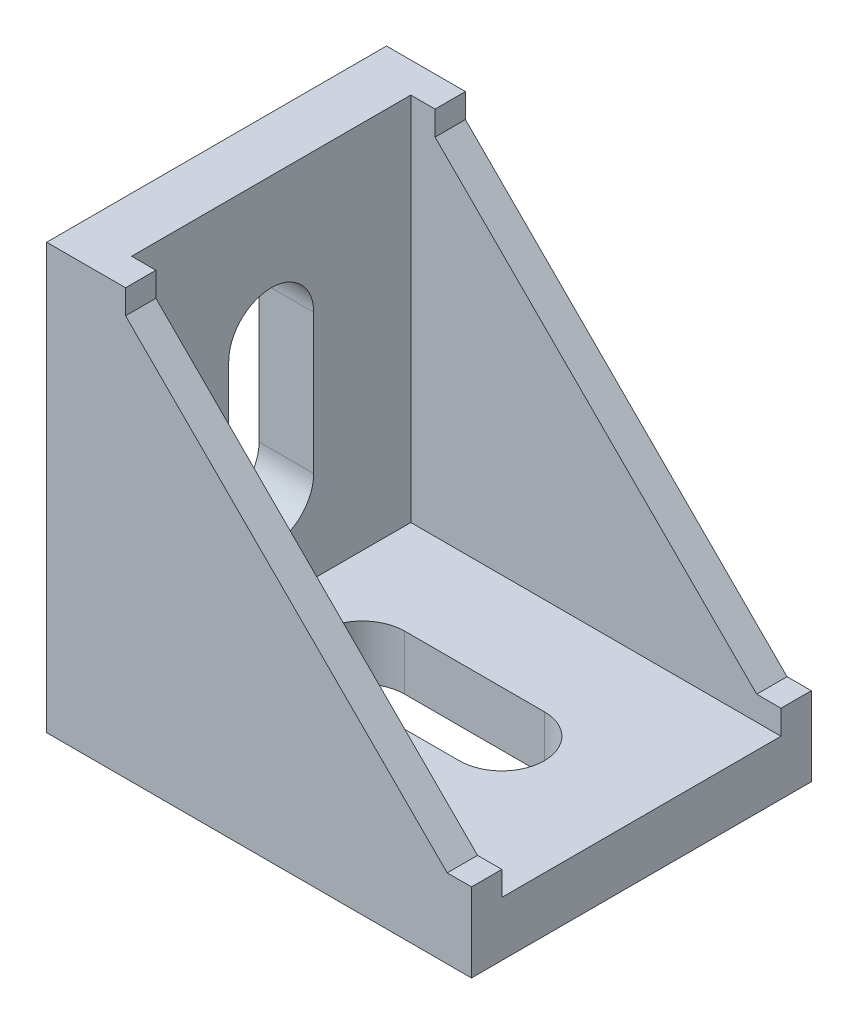
SolidWorks part; units mm, degrees
ref_plane "Front Plane" through (0, 0, 0) normal (0, 0, 1) x (1, 0, 0)
ref_plane "Top Plane" through (0, 0, 0) normal (0, 1, 0) x (1, 0, 0)
ref_plane "Right Plane" through (0, 0, 0) normal (1, 0, 0) x (0, 0, -1)
sketch "Sketch1" plane through (0, 0, 0) normal (0, 0, 1) x (1, 0, 0)
  line L1 (0, 0) -> (35, 0)
  line L2 (0, 0) -> (0, 35)
  line L3 (0, 35) -> (35, 35)
  line L4 (35, 0) -> (35, 35)
extrude "Boss-Extrude1" add sketch "Sketch1" along normal blind 28
sketch "Sketch2" plane through (0, 0, 28) normal (0, 0, 1) x (1, 0, 0)
  line L2 (6.5, 35) -> (6.5, 0)
  line L3 (6.5, 37.082) -> (6.5, 33)
  line L5 (6.5, 37.082) -> (39.7013, 37.082)
  line L6 (39.7013, 37.082) -> (39.7013, 6.5)
  line L10 (6.5, 33) -> (33, 6.5)
  line L13 (33, 6.5) -> (39.7013, 6.5)
  dimension "D1" = 6.5
extrude "Cut-Extrude1" cut sketch "Sketch2" against normal through all
ref_plane "Plane1" through (4.5, 0, 0) normal (-1, 0, 0) x (0, 0, 1)
sketch "Sketch3" plane through (4.5, 0, 0) normal (-1, 0, 0) x (0, 0, 1)
  line L2 (28, 4.5) -> (0, 4.5)
  line L3 (25.5, 4.5) -> (2.5, 4.5)
  line L5 (25.5, 33) -> (25.5, 6.5)
  line L6 (25.5, 38.217) -> (25.5, 4.5)
  line L7 (25.5, 38.217) -> (2.5, 38.217)
  line L8 (2.5, 33) -> (2.5, 6.5)
  line L9 (2.5, 38.217) -> (2.5, 4.5)
  dimension "D1" = 4.5
  dimension "D2" = 2.5
  dimension "D3" = 2.5
extrude "Cut-Extrude2" cut sketch "Sketch3" against normal up to surface (30.5 mm away) up to face at (35, 3.25, 14)
sketch "Sketch4" plane through (4.5, 0, 0) normal (1, 0, 0) x (0, 0, -1)
  line L4 (-10.5, 23.5) -> (-10.5, 12)
  line L5 (-17.5, 12) -> (-17.5, 23.5)
  arc A0 (-10.5, 23.5) -> (-17.5, 23.5) centre (-14, 23.5) ccw
  arc A1 (-17.5, 12) -> (-10.5, 12) centre (-14, 12) ccw
extrude "Cut-Extrude3" cut sketch "Sketch4" against normal up to surface (4.5 mm away) up to face at (0, 17.5, 14)
sketch "Sketch5" plane through (0, 4.5, 0) normal (0, 1, 0) x (1, 0, 0)
  line L4 (23.5, -17.5) -> (12, -17.5)
  line L5 (12, -10.5) -> (23.5, -10.5)
  arc A0 (23.5, -17.5) -> (23.5, -10.5) centre (23.5, -14) ccw
  arc A1 (12, -10.5) -> (12, -17.5) centre (12, -14) ccw
extrude "Cut-Extrude4" cut sketch "Sketch5" against normal up to surface (4.5 mm away) up to face at (17.5, 0, 14)
sketch "Sketch6" plane through (0, 0, 0) normal (0, -1, 0) x (1, 0, 0)
  line L1 (33, 16.9) -> (33, 11.1)
  line L3 (34, 16.9) -> (34, 11.1)
  line L4 (34, 28) -> (34, 0) construction
  line L5 (34, 16.9) -> (33, 16.9)
  line L6 (34, 11.1) -> (33, 11.1)
  line L7 (33, 28) -> (33, 0) construction
extrude "Boss-Extrude2" add sketch "Sketch6" along normal blind 1
sketch "Sketch7" plane through (0, 0, 0) normal (-1, 0, 0) x (0, 0, 1)
  line L5 (16.9, 33) -> (11.1, 33)
  line L6 (28, 34) -> (0, 34)
  line L7 (16.9, 34) -> (11.1, 34)
  line L9 (11.1, 34) -> (11.1, 33)
  line L10 (16.9, 34) -> (16.9, 33)
  line L12 (28, 34) -> (0, 34) construction
  line L13 (28, 33) -> (0, 33) construction
  dimension "D1" = 1
  dimension "D2" = 1
extrude "Boss-Extrude3" add sketch "Sketch7" along normal blind 1
